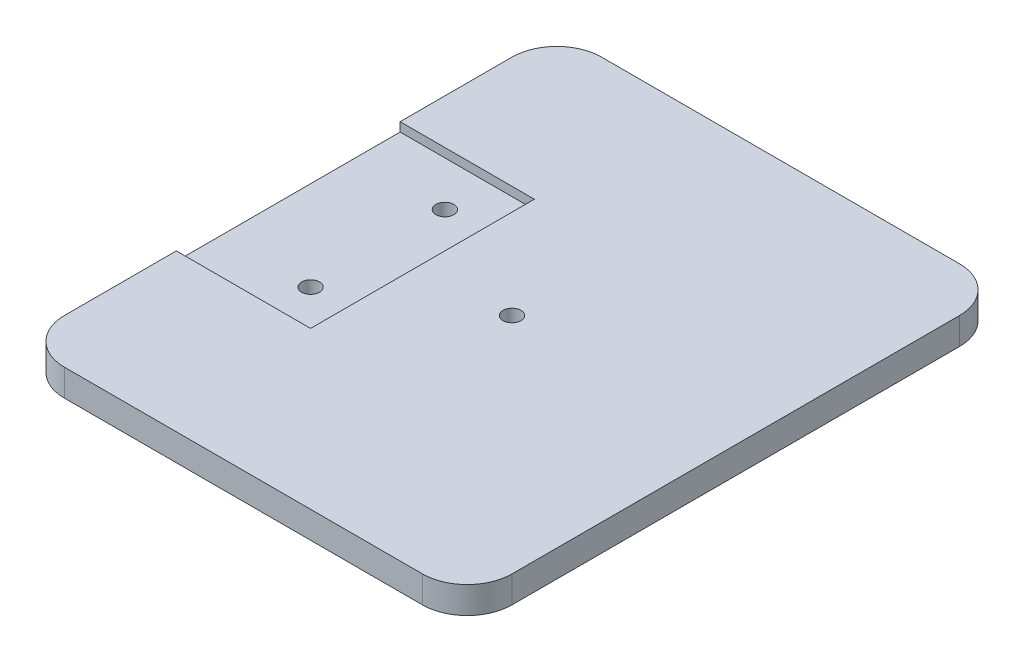
SolidWorks part; units mm, degrees
ref_plane "Front Plane" through (0, 0, 0) normal (0, 0, 1) x (1, 0, 0)
ref_plane "Top Plane" through (0, 0, 0) normal (0, 1, 0) x (1, 0, 0)
ref_plane "Right Plane" through (0, 0, 0) normal (1, 0, 0) x (0, 0, -1)
sketch "Sketch1" plane through (0, 0, 0) normal (0, 1, 0) x (1, 0, 0)
  line L1 (-52.2549, 26.2745) -> (-12.2549, 26.2745)
  line L2 (-57.2549, 21.2745) -> (-57.2549, -28.7255)
  line L3 (-52.2549, -33.7255) -> (-12.2549, -33.7255)
  line L4 (-7.2549, 21.2745) -> (-7.2549, -28.7255)
  arc A0 (-57.2549, -28.7255) -> (-52.2549, -33.7255) centre (-52.2549, -28.7255) ccw
  arc A1 (-12.2549, -33.7255) -> (-7.2549, -28.7255) centre (-12.2549, -28.7255) ccw
  arc A2 (-12.2549, 26.2745) -> (-7.2549, 21.2745) centre (-12.2549, 21.2745) cw
  arc A3 (-52.2549, 26.2745) -> (-57.2549, 21.2745) centre (-52.2549, 21.2745) ccw
  circle A4 centre (-32.2549, -3.7255) radius 1
  circle A5 centre (-47.2549, 3.7745) radius 1
  circle A6 centre (-47.2549, -11.2255) radius 1
  point P6 (-57.2549, -33.7255)
  point P11 (-7.2549, 26.2745)
  point P14 (-57.2549, 26.2745)
  dimension "D3" = 5
  dimension "D4" = 30
  dimension "D6" = 22.5
  dimension "D8" = 15
  dimension "D1" = 60
  dimension "D2" = 50
  dimension "D5" = 25
  dimension "D7" = 10
  dimension "D9" = 10
extrude "Boss-Extrude1" add sketch "Sketch1" along normal blind 3
sketch "Sketch2" plane through (0, 3, 0) normal (0, 1, 0) x (1, 0, 0)
  line L0 (-57.2549, 21.2745) -> (-57.2549, -28.7255) construction
  line L1 (-57.2549, 8.7745) -> (-42.2549, 8.7745)
  line L2 (-57.2549, 8.7745) -> (-57.2549, -16.2255)
  line L3 (-57.2549, -16.2255) -> (-42.2549, -16.2255)
  line L4 (-42.2549, 8.7745) -> (-42.2549, -16.2255)
  line L5 (-12.2549, 26.2745) -> (-52.2549, 26.2745) construction
  line L6 (-52.2549, -33.7255) -> (-12.2549, -33.7255) construction
  dimension "D1" = 17.5
  dimension "D2" = 17.5
  dimension "D3" = 15
extrude "Cut-Extrude1" cut sketch "Sketch2" against normal blind 1 contours L2 L1 L4 L3
